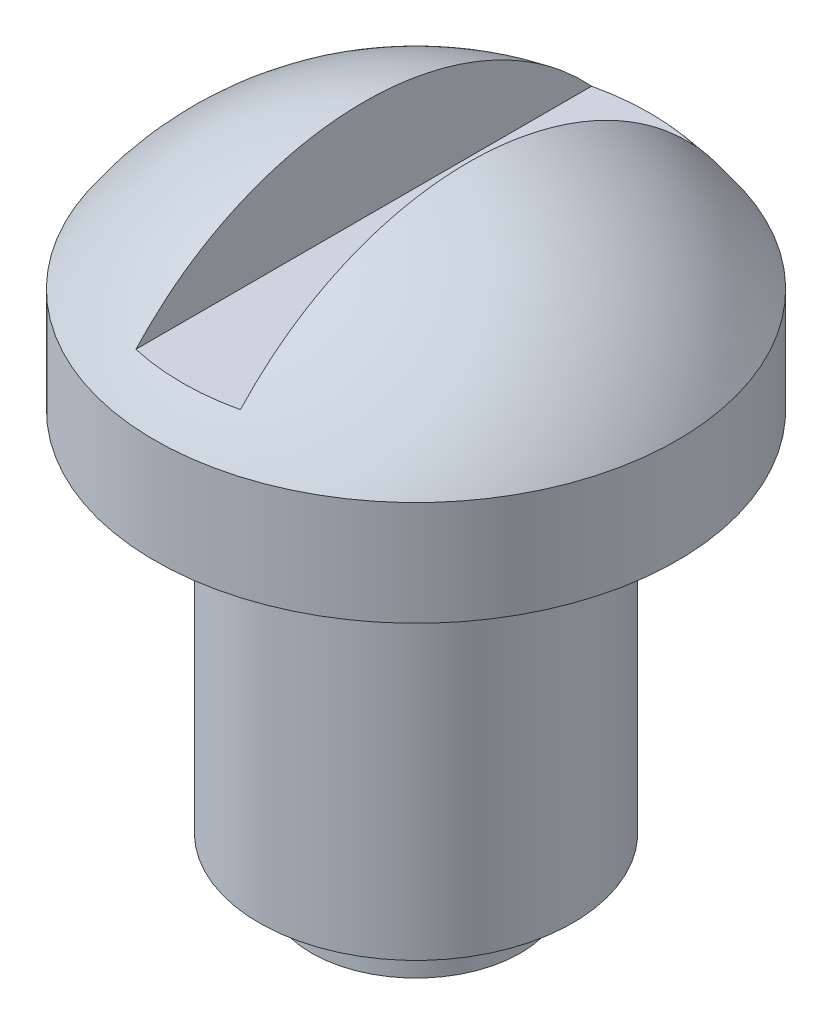
SolidWorks part; units mm, degrees
material "AISI 1020"
ref_plane "Front Plane" through (0, 0, 0) normal (0, 0, 1) x (1, 0, 0)
ref_plane "Top Plane" through (0, 0, 0) normal (0, 1, 0) x (1, 0, 0)
ref_plane "Right Plane" through (0, 0, 0) normal (1, 0, 0) x (0, 0, -1)
sketch "Sketch1" plane through (0, 0, 0) normal (0, 0, 1) x (1, 0, 0)
  line L0 (0, 0) -> (0, -12.6834)
  line L1 (0, -12.6834) -> (2, -12.6834)
  line L2 (2, -12.6834) -> (2, -11.6834)
  line L3 (2, -11.6834) -> (3, -11.6834)
  line L4 (3, -11.6834) -> (3, -4.6834)
  line L5 (3, -4.6834) -> (5, -4.6834)
  line L6 (5, -4.6834) -> (5, -2.6834)
  arc A0 (0, 0) -> (5, -2.6834) centre (0, -6) cw
  dimension "D6" = 6
  dimension "D1" = 2
  dimension "D2" = 3
  dimension "D3" = 1
  dimension "D4" = 7
  dimension "D5" = 5
  dimension "2" = 2
revolve "Revolve1" add sketch "Sketch1" angle 360 about L0
sketch "Sketch2" plane through (0, 0, 0) normal (0, 0, 1) x (1, 0, 0)
  line L1 (-1, 2) -> (1, 2)
  line L2 (-1, 2) -> (-1, -2)
  line L3 (-1, -2) -> (1, -2)
  line L4 (1, 2) -> (1, -2)
  line L5 (-1, 2) -> (1, -2) construction
  line L6 (-1, -2) -> (1, 2) construction
  point P0 (0, 0)
  dimension "D1" = 2
  dimension "D2" = 2
extrude "Cut-Extrude1" cut sketch "Sketch2" against normal mid plane 10
